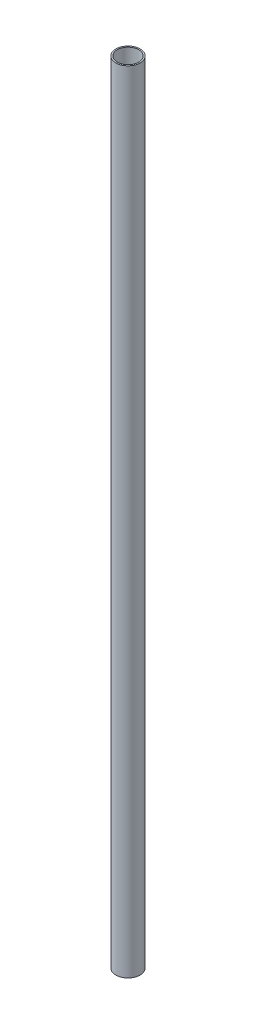
SolidWorks part; units mm, degrees
ref_plane "Front Plane" through (0, 0, 0) normal (0, 0, 1) x (1, 0, 0)
ref_plane "Top Plane" through (0, 0, 0) normal (0, 1, 0) x (1, 0, 0)
ref_plane "Right Plane" through (0, 0, 0) normal (1, 0, 0) x (0, 0, -1)
sketch "Sketch1" plane through (0, 0, 0) normal (0, 1, 0) x (1, 0, 0)
  circle A0 centre (0, 0) radius 20
  circle A1 centre (0, 0) radius 17.7
  dimension "D1" = 40
  dimension "D2" = 2.3
extrude "Boss-Extrude1" add sketch "Sketch1" along normal blind 1300
